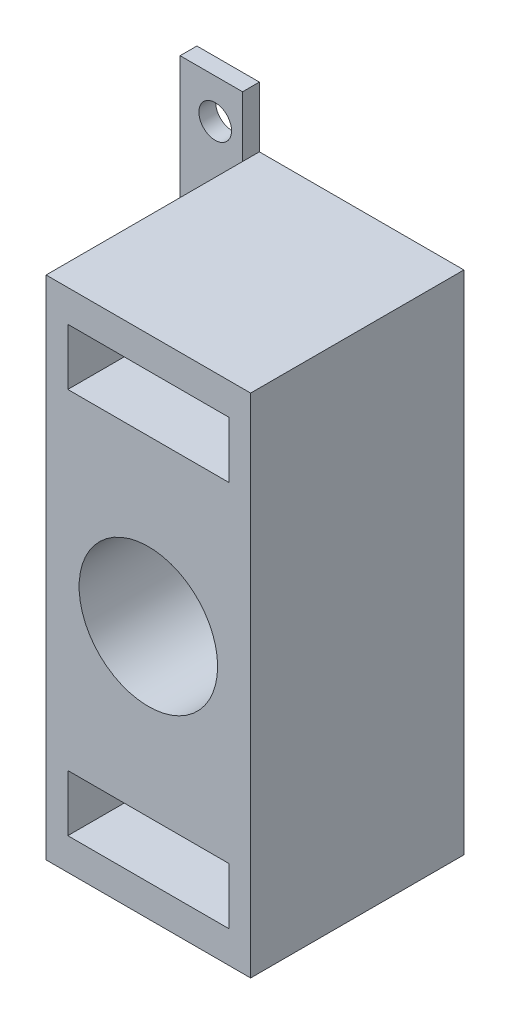
SolidWorks part; units mm, degrees
ref_plane "Front Plane" through (0, 0, 0) normal (0, 0, 1) x (1, 0, 0)
ref_plane "Top Plane" through (0, 0, 0) normal (0, 1, 0) x (1, 0, 0)
ref_plane "Right Plane" through (0, 0, 0) normal (1, 0, 0) x (0, 0, -1)
sketch "Sketch1" plane through (0, 0, 0) normal (0, 0, 1) x (1, 0, 0)
  line L0 (0, 75.4142) -> (0, -75.4142) construction
  line L1 (-30.45, 75.4142) -> (30.45, 75.4142)
  line L2 (-30.45, 75.4142) -> (-30.45, -75.4142)
  line L3 (-30.45, -75.4142) -> (30.45, -75.4142)
  line L4 (30.45, 75.4142) -> (30.45, -75.4142)
  line L5 (-156.0685, 0) -> (156.0685, 0) construction
  line L6 (-23.9859, -49.1269) -> (23.9859, -49.1269)
  line L7 (-23.9859, 65.9335) -> (23.9859, 65.9335)
  line L12 (-23.9859, 65.9335) -> (-23.9859, 49.1269)
  line L13 (-23.9859, 49.1269) -> (23.9859, 49.1269)
  line L14 (23.9859, 65.9335) -> (23.9859, 49.1269)
  line L15 (23.9859, -65.9335) -> (23.9859, -49.1269)
  line L16 (-23.9859, -65.9335) -> (23.9859, -65.9335)
  line L17 (-23.9859, -65.9335) -> (-23.9859, -49.1269)
  circle A0 centre (0, 0) radius 20.6182
  point P0 (0, 0)
  point P6 (0, 57.5302)
  point P9 (0, 0)
  point P17 (0, 0)
extrude "Boss-Extrude1" add sketch "Sketch1" along normal blind 63.5
sketch "Sketch2" plane through (0, 0, 0) normal (0, 0, -1) x (-1, 0, 0)
  line L0 (0, 0) -> (110.5366, 0) construction
  line L1 (30.45, 75.4142) -> (30.45, 93.4052)
  line L2 (30.45, 93.4052) -> (49.0484, 93.4052)
  line L3 (49.0484, 93.4052) -> (49.0484, 0)
  line L4 (-30.45, 75.4142) -> (-30.45, -75.4142)
  line L5 (-30.45, -75.4142) -> (30.45, -75.4142)
  line L6 (30.45, -75.4142) -> (30.45, 75.4142)
  line L7 (30.45, 75.4142) -> (-30.45, 75.4142)
  line L8 (-30.45, 75.4142) -> (-30.45, -75.4142)
  line L9 (-30.45, -75.4142) -> (30.45, -75.4142)
  line L10 (30.45, -75.4142) -> (30.45, 75.4142)
  line L11 (30.45, 75.4142) -> (-30.45, 75.4142)
  line L12 (49.0484, 0) -> (30.45, 0)
  circle A0 centre (38.599, 81.6763) radius 4.8629
  circle A1 centre (38.599, 34.9736) radius 5.3823
  dimension "D1" = 0
extrude "Boss-Extrude2" add sketch "Sketch2" against normal blind 5 contours L12 L3 L2 L1 L10 A1 A0
